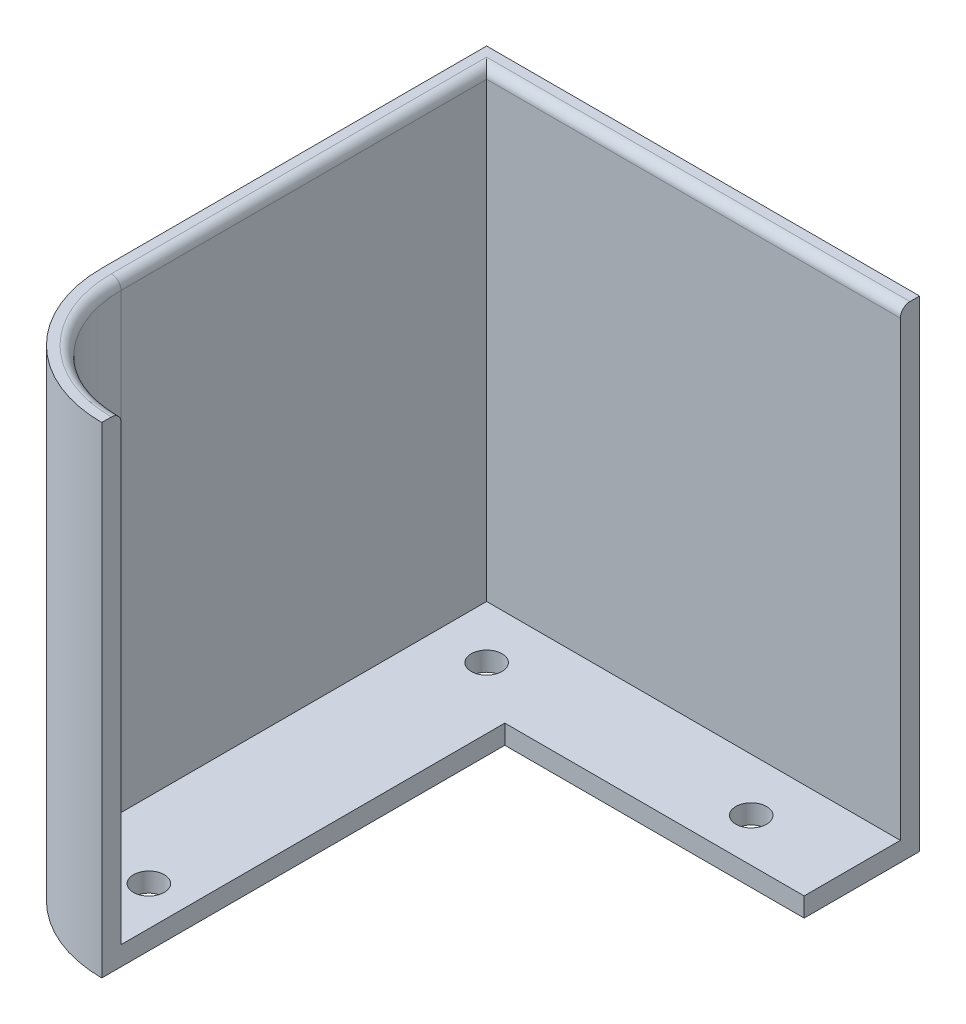
SolidWorks part; units mm, degrees
ref_plane "Front Plane" through (0, 0, 0) normal (0, 0, 1) x (1, 0, 0)
ref_plane "Top Plane" through (0, 0, 0) normal (0, 1, 0) x (1, 0, 0)
ref_plane "Right Plane" through (0, 0, 0) normal (1, 0, 0) x (0, 0, -1)
sketch "Sketch1" plane through (0, 0, 0) normal (0, 1, 0) x (1, 0, 0)
  line L0 (789.1479, -65.4048) -> (789.1479, -25.4048)
  line L1 (789.1479, -25.4048) -> (834.1479, -25.4048)
  line L2 (834.1479, -25.4048) -> (834.1479, -37.4048)
  line L3 (834.1479, -37.4048) -> (803.0379, -37.4048)
  line L4 (803.0379, -37.4048) -> (803.0379, -58.8073)
  line L5 (803.0379, -58.8073) -> (803.0379, -79.2948)
  arc A0 (789.1479, -65.4048) -> (803.0379, -79.2948) centre (803.0379, -65.4048) ccw
  dimension "D3" = 13.89
  dimension "D1" = 45
  dimension "D2" = 40
  dimension "D4" = 12
  dimension "D5" = 13.89
extrude "Boss-Extrude1" add sketch "Sketch1" along normal blind 50
sketch "Sketch2" plane through (0, 50, 0) normal (0, 1, 0) x (1, 0, 0)
  line L0 (834.1479, -27.4048) -> (791.1479, -27.4048)
  line L1 (834.1479, -37.4048) -> (834.1479, -25.4048) construction
  line L2 (791.1479, -27.4048) -> (791.1479, -65.4048)
  line L3 (834.1479, -27.4048) -> (834.1479, -63.2764)
  line L4 (789.1479, -25.4048) -> (789.1479, -65.4048) construction
  line L5 (789.1479, -25.4048) -> (834.1479, -25.4048) construction
  line L6 (803.0379, -79.2948) -> (803.0379, -37.4048) construction
  line L7 (834.1479, -63.2764) -> (803.0379, -77.2929)
  arc A0 (791.1479, -65.4048) -> (803.0379, -77.2929) centre (803.0361, -65.4048) ccw
  dimension "D1" = 2
  dimension "D2" = 2
  dimension "D3" = 38
extrude "Cut-Extrude1" cut sketch "Sketch2" against normal blind 48
sketch "Sketch3" plane through (0, 2, 0) normal (0, 1, 0) x (1, 0, 0)
  line L0 (834.1479, -25.4048) -> (789.1479, -25.4048) construction
  line L1 (834.1479, -37.4048) -> (834.1479, -27.4048) construction
  line L2 (789.1479, -25.4048) -> (789.1479, -65.4048) construction
  circle A0 centre (824.1479, -32.9048) radius 1.6
  circle A1 centre (796.6479, -32.9048) radius 1.6
  circle A2 centre (798.9829, -70.3448) radius 1.6
  arc A6 (789.1479, -65.4048) -> (803.0361, -79.2929) centre (803.0361, -65.4048) ccw construction
  dimension "D1" = 3.2
  dimension "D2" = 3.2
  dimension "D3" = 3.2
  dimension "D4" = 7.5
  dimension "D5" = 10
  dimension "D6" = 7.5
  dimension "D7" = 7.5
  dimension "D8" = 37.44
  dimension "D9" = 6.39
extrude "Cut-Extrude2" cut sketch "Sketch3" against normal through all
fillet "Fillet3" radius 1 3 edges at (791.1479, 50, 46.4048) (812.6479, 50, 27.4048) (794.6306, 50, 73.8117)
